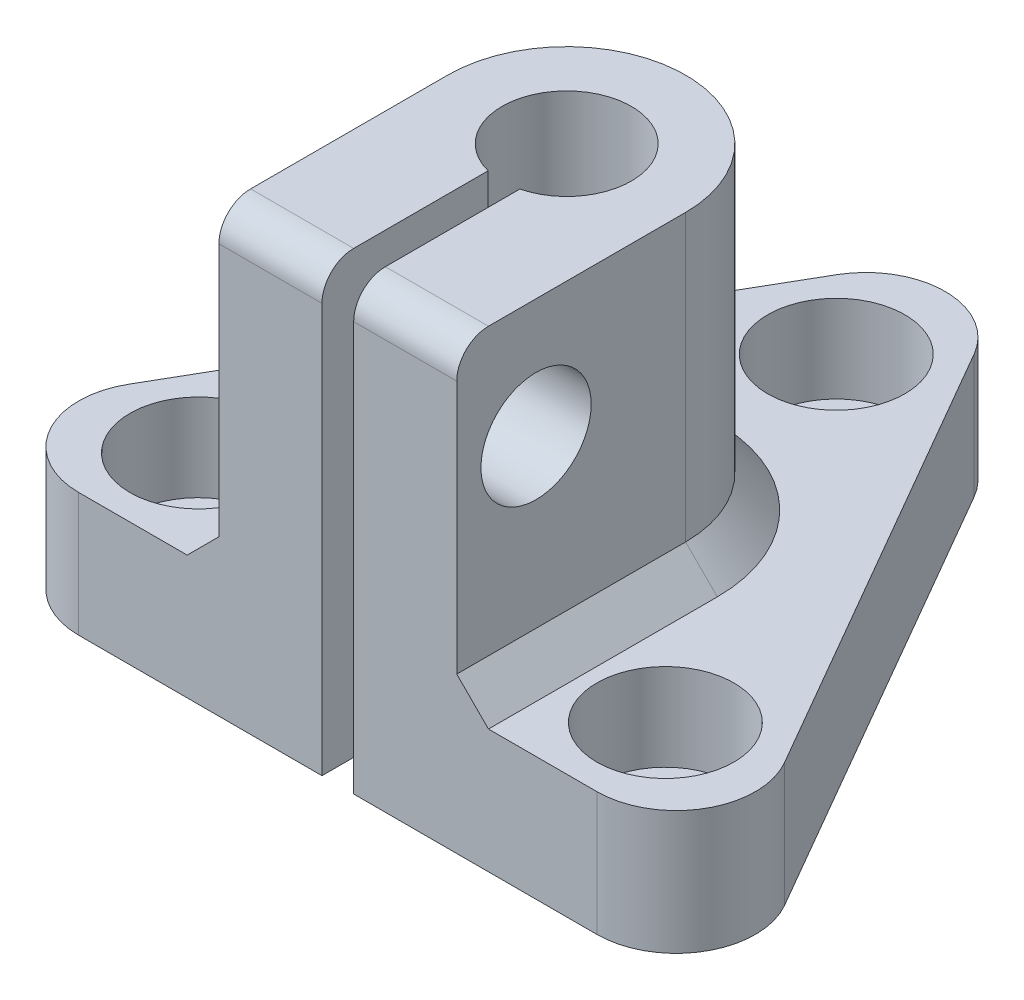
SolidWorks part; units mm, degrees
ref_plane "Plan de face" through (0, 0, 0) normal (0, 0, 1) x (1, 0, 0)
ref_plane "Plan de dessus" through (0, 0, 0) normal (0, 1, 0) x (1, 0, 0)
ref_plane "Plan de droite" through (0, 0, 0) normal (1, 0, 0) x (0, 0, -1)
sketch "Esquisse5" plane through (0, 0, 0) normal (0, 1, 0) x (1, 0, 0)
  line L0 (-25, -14.4338) -> (25, -14.4338)
  line L1 (25, -14.4338) -> (0, 28.8675)
  line L2 (0, 28.8675) -> (-25, -14.4338)
  line L3 (12.5, 7.2169) -> (-25, -14.4338) construction
  line L4 (-12.5, 7.2169) -> (25, -14.4338) construction
  circle A0 centre (0, 17) radius 2.575
  circle A1 centre (-14.7224, -8.5) radius 2.575
  circle A2 centre (14.7224, -8.5) radius 2.575
  dimension "D1" = 5.15
  dimension "D2" = 17
  dimension "D3" = 17
  dimension "D4" = 17
  dimension "D5" = 50
extrude "Boss.-Extru.2" add sketch "Esquisse5" along normal blind 7.8
sketch "Esquisse6" plane through (0, 7.8, 0) normal (0, 1, 0) x (1, 0, 0)
  circle A0 centre (0, 0) radius 7.5
  dimension "D1" = 15
extrude "Boss.-Extru.3" add sketch "Esquisse6" along normal blind 20
sketch "Esquisse13" plane through (0, 27.8, 0) normal (0, 1, 0) x (1, 0, 0)
  line L1 (-7.5, 0) -> (-7.5, -14.4338)
  line L2 (7.5, 0) -> (7.5, -14.4338)
  line L3 (-7.5, -14.4338) -> (7.5, -14.4338)
  line L4 (-25, -14.4338) -> (25, -14.4338) construction
  circle A0 centre (0, 0) radius 7.5 construction
  circle A1 centre (0, 0) radius 7.5 construction
  arc A2 (-7.5, 0) -> (7.5, 0) centre (0, 0) ccw
  point P8 (0, -14.4338)
extrude "Boss.-Extru.6" add sketch "Esquisse13" against normal up to surface (20 mm away) up to face at (0, 7.8, 7.5)
sketch "Esquisse14" plane through (0, 27.8, 0) normal (0, 1, 0) x (1, 0, 0)
  circle A0 centre (0, 0) radius 4.08
  dimension "D1" = 8.16
extrude "Enlèv. mat.-Extru.4" cut sketch "Esquisse14" against normal through all
sketch "Esquisse15" plane through (0, 27.8, 0) normal (0, 1, 0) x (1, 0, 0)
  line L1 (-1, -3.9556) -> (-1, -14.4338)
  line L2 (1, -3.9556) -> (1, -14.4338)
  line L3 (-1, -14.4338) -> (1, -14.4338)
  line L4 (-7.5, -14.4338) -> (7.5, -14.4338) construction
  circle A0 centre (0, 0) radius 4.08 construction
  arc A1 (-1, -3.9556) -> (1, -3.9556) centre (0, 0) ccw
  dimension "D1" = 2
extrude "Enlèv. mat.-Extru.5" cut sketch "Esquisse15" against normal through all
fillet "Congé2" radius 5 3 edges at (0, 3.9, -28.8675) (-25, 3.9, 14.4338) (25, 3.9, 14.4338)
sketch "Esquisse17" plane through (7.5, 0, 0) normal (1, 0, 0) x (0, 0, -1)
  line L0 (-14.4338, 27.8) -> (0, 27.8) construction
  line L1 (-14.4338, 7.8) -> (-14.4338, 27.8) construction
  circle A0 centre (-9.4338, 20.3) radius 2.05
  dimension "D1" = 4.1
  dimension "D2" = 7.5
  dimension "D3" = 5
extrude "Enlèv. mat.-Extru.6" cut sketch "Esquisse17" against normal through all
sketch "Esquisse18" plane through (-7.5, 0, 0) normal (-1, 0, 0) x (0, 0, 1)
  line L0 (0, 27.8) -> (14.4338, 27.8) construction
  line L1 (11.4689, 23.825) -> (7.3986, 23.825)
  line L2 (7.3986, 23.825) -> (5.3634, 20.3)
  line L3 (5.3634, 20.3) -> (7.3986, 16.775)
  line L4 (7.3986, 16.775) -> (11.4689, 16.775)
  line L5 (11.4689, 16.775) -> (13.5041, 20.3)
  line L6 (13.5041, 20.3) -> (11.4689, 23.825)
  circle A0 centre (9.4338, 20.3) radius 3.525 construction
  dimension "D1" = 7.05
extrude "Enlèv. mat.-Extru.7" cut sketch "Esquisse18" against normal blind 3.25
sketch "Esquisse19" plane through (0, 7.8, 0) normal (0, 1, 0) x (1, 0, 0)
  circle A0 centre (0, 17) radius 4.325
  circle A1 centre (14.7224, -8.5) radius 4.325
  circle A2 centre (-14.7224, -8.5) radius 4.325
  dimension "D1" = 8.65
extrude "Enlèv. mat.-Extru.8" cut sketch "Esquisse19" against normal blind 5.5
sketch "Esquisse20" plane through (7.5, 0, 0) normal (1, 0, 0) x (0, 0, -1)
  circle A0 centre (-9.4338, 20.3) radius 3.475
  dimension "D1" = 6.95
extrude "Enlèv. mat.-Extru.9" cut sketch "Esquisse20" against normal blind 4.97
fillet "Congé3" radius 2 2 edges at (-4.25, 27.8, 14.4338) (4.25, 27.8, 14.4338)
chamfer "Chanfrein2" distance 2 angle 45 3 edges at (-7.5, 7.8, 7.2169) (0, 7.8, -7.5) (7.5, 7.8, 7.2169)
